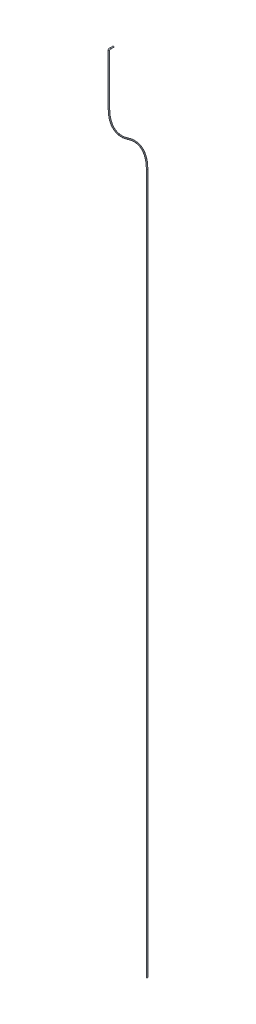
SolidWorks part; units mm, degrees
ref_plane "Front Plane" through (0, 0, 0) normal (0, 0, 1) x (1, 0, 0)
ref_plane "Top Plane" through (0, 0, 0) normal (0, 1, 0) x (1, 0, 0)
ref_plane "Right Plane" through (0, 0, 0) normal (1, 0, 0) x (0, 0, -1)
sketch "Illustrative smooth utility route" plane through (0, 0, 0) normal (1, 0, 0) x (0, 0, -1)
  line L0 (-15.85, 0) -> (-17.05, 0)
  line L1 (-17.35, -0.3) -> (-17.35, -17.32)
  line L2 (-4.5, -41.32) -> (-4.5, -277.32)
  arc A0 (-17.05, 0) -> (-17.35, -0.3) centre (-17.05, -0.3) ccw
  arc A1 (-17.35, -17.32) -> (-10.925, -29.32) centre (-2.9313, -17.32) ccw
  arc A2 (-10.925, -29.32) -> (-4.5, -41.32) centre (-18.9187, -41.32) cw
sketch "Utility circular cross section" plane through (0, 0, 0) normal (0, 1, 0) x (1, 0, 0)
  circle A0 centre (0, -17.35) radius 0.18
sweep "Native hollow utility sweep" add path "Illustrative smooth utility route" circular profile diameter 0.36 parameters "D3"=0.36
